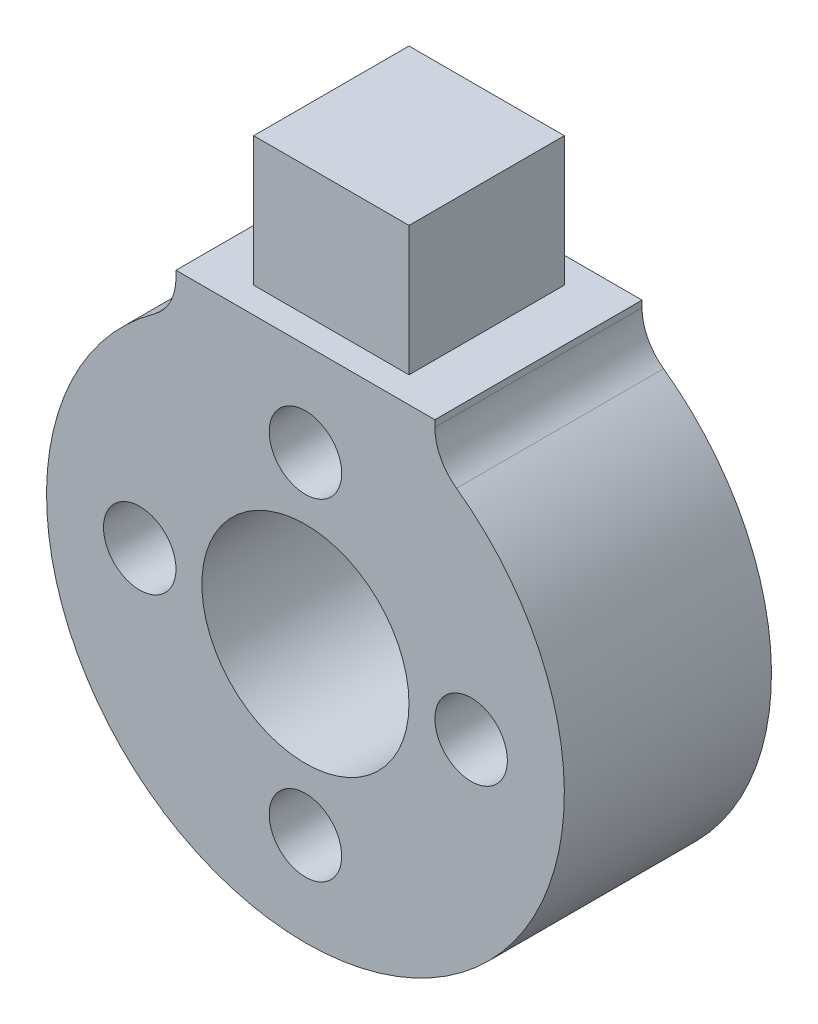
SolidWorks part; units mm, degrees
ref_plane "Front Plane" through (0, 0, 0) normal (0, 0, 1) x (1, 0, 0)
ref_plane "Top Plane" through (0, 0, 0) normal (0, 1, 0) x (1, 0, 0)
ref_plane "Right Plane" through (0, 0, 0) normal (1, 0, 0) x (0, 0, -1)
sketch "Sketch1" plane through (0, 0, 0) normal (0, 0, 1) x (1, 0, 0)
  line L0 (0, 0) -> (0, 127) construction
  line L1 (-6.35, 12.7) -> (-6.35, 10.9985)
  line L2 (-6.35, 12.7) -> (6.35, 12.7)
  line L3 (6.35, 12.7) -> (6.35, 10.9985)
  circle A0 centre (0, 0) radius 5.08
  arc A1 (-6.35, 10.9985) -> (6.35, 10.9985) centre (0, 0) ccw
  circle A2 centre (0, 8.128) radius 1.778
  circle A3 centre (8.128, 0) radius 1.778
  circle A4 centre (0, -8.128) radius 1.778
  circle A5 centre (-8.128, 0) radius 1.778
  point P15 (0, 0)
  dimension "D1" = 10.16
  dimension "D2" = 25.4
  dimension "D4" = 3.556
  dimension "D3" = 8.128
  dimension "D8" = 1.7015
  dimension "D9" = 1.7015
  dimension "D5" = 4
extrude "Boss-Extrude1" add sketch "Sketch1" along normal blind 10.16
fillet "Fillet1" radius 2.54 2 edges at (6.35, 10.9985, 5.08) (-6.35, 10.9985, 5.08)
sketch "Sketch2" plane through (0, 12.7, 0) normal (0, 1, 0) x (1, 0, 0)
  line L0 (6.35, -10.16) -> (6.35, 0) construction
  line L1 (-3.81, -8.89) -> (3.81, -8.89)
  line L2 (-3.81, -8.89) -> (-3.81, -1.27)
  line L3 (-3.81, -1.27) -> (3.81, -1.27)
  line L4 (3.81, -8.89) -> (3.81, -1.27)
  line L5 (-3.81, -8.89) -> (3.81, -1.27) construction
  line L6 (-3.81, -1.27) -> (3.81, -8.89) construction
  line L7 (-6.35, 0) -> (6.35, 0) construction
  point P0 (0, -5.08)
  dimension "D1" = 7.62
  dimension "D2" = 7.62
  dimension "D3" = 2.54
  dimension "D4" = 1.27
extrude "Boss-Extrude3" add sketch "Sketch2" along normal blind 6.35
